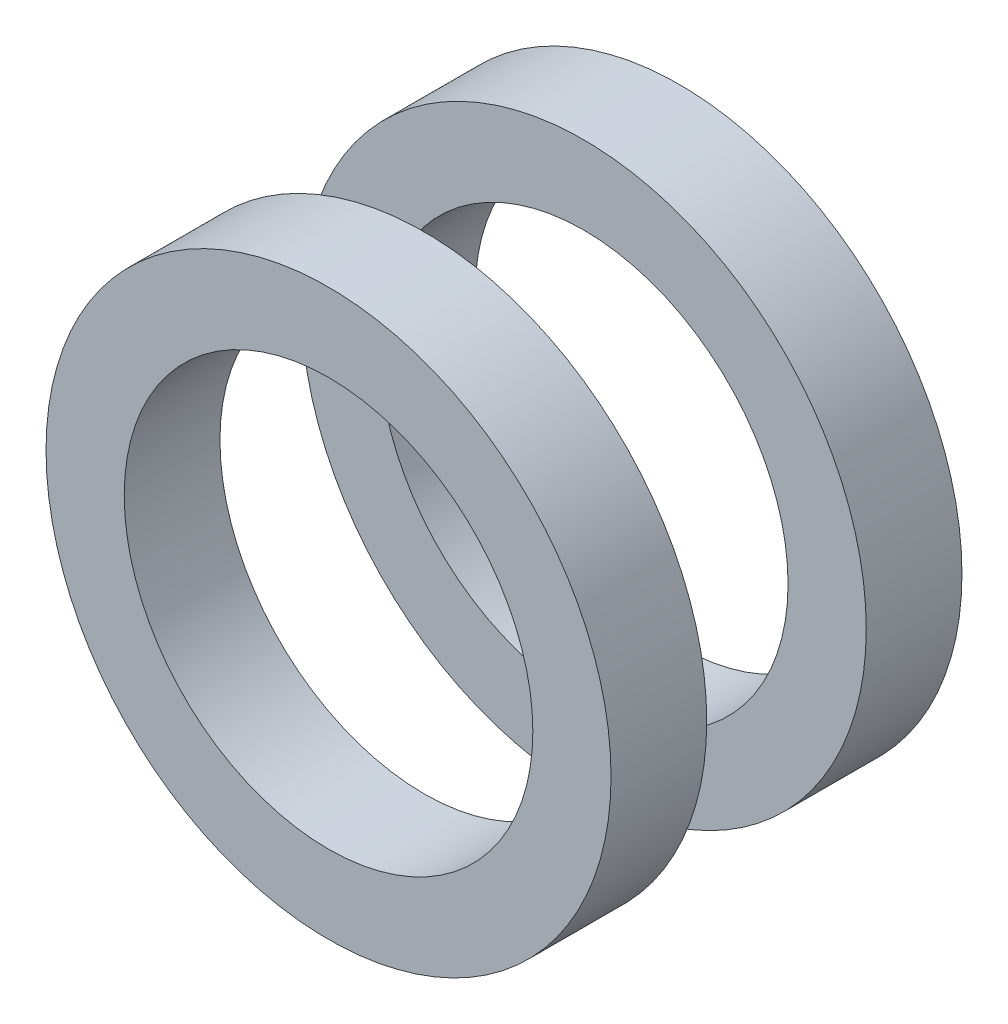
SolidWorks part; units mm, degrees
ref_plane "Спереди" through (0, 0, 0) normal (0, 0, 1) x (1, 0, 0)
ref_plane "Сверху" through (0, 0, 0) normal (0, 1, 0) x (1, 0, 0)
ref_plane "Справа" through (0, 0, 0) normal (1, 0, 0) x (0, 0, -1)
sketch "Эскиз1" plane through (0, 0, 0) normal (0, 0, 1) x (1, 0, 0)
  circle A0 centre (0, 0) radius 53.1308
  circle A1 centre (0, 0) radius 38.4231
extrude "Endturn_R" add sketch "Эскиз1" along normal blind 18 from offset 15 separate body
sketch "Эскиз2" plane through (0, 0, 0) normal (0, 0, 1) x (1, 0, 0)
  circle A0 centre (0, 0) radius 53.1308
  circle A1 centre (0, 0) radius 38.4231
extrude "Endturn_L" add sketch "Эскиз2" along normal blind 18 from offset 33 separate body
